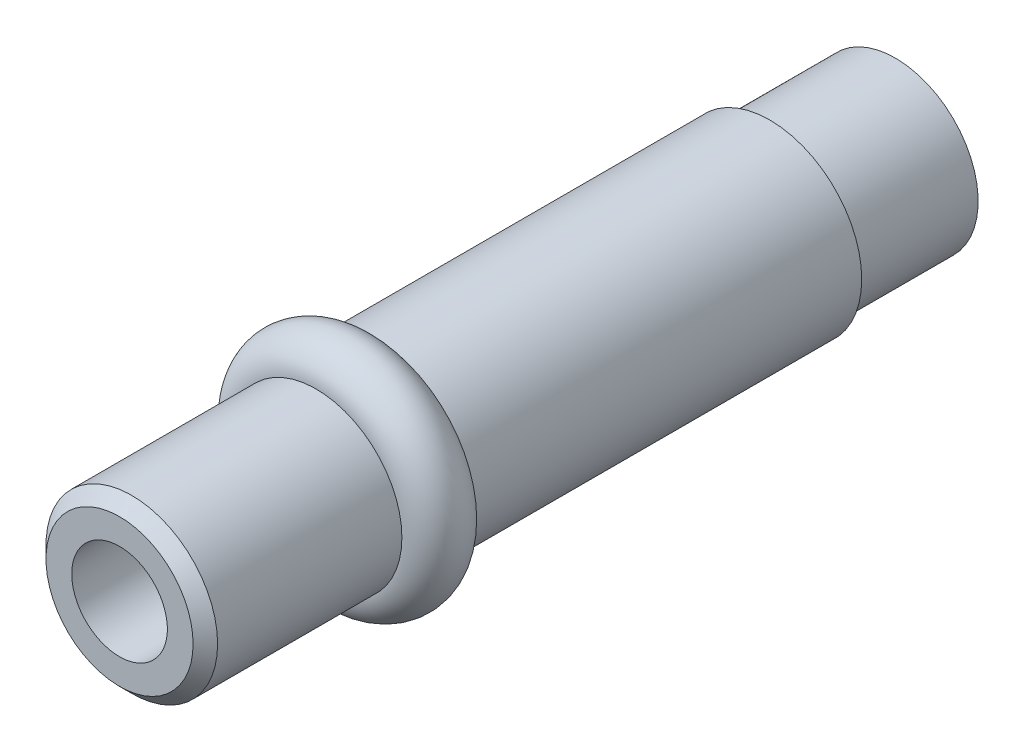
SolidWorks part; units mm, degrees
material "Plain Carbon Steel"
ref_plane "Front Plane" through (0, 0, 0) normal (0, 0, 1) x (1, 0, 0)
ref_plane "Top Plane" through (0, 0, 0) normal (0, 1, 0) x (1, 0, 0)
ref_plane "Right Plane" through (0, 0, 0) normal (1, 0, 0) x (0, 0, -1)
sketch "Sketch1" plane through (0, 0, 0) normal (0, 0, 1) x (1, 0, 0)
  circle A0 centre (0, 0) radius 3.81
  dimension "D1" = 7.62
extrude "Boss-Extrude1" add sketch "Sketch1" along normal blind 32.1564
sketch "Sketch2" plane through (0, 0, 0) normal (0, 0, -1) x (-1, 0, 0)
  circle A0 centre (0, 0) radius 1.9812
  dimension "D1" = 3.9624
extrude "Cut-Extrude1" cut sketch "Sketch2" against normal through all
sketch "Sketch3" plane through (0, 0, 0) normal (0, 0, -1) x (-1, 0, 0)
  circle A0 centre (0, 0) radius 3.429
  circle A1 centre (0, 0) radius 3.81 construction
  circle A2 centre (0, 0) radius 3.81
  dimension "D1" = 6.858
extrude "Cut-Extrude2" cut sketch "Sketch3" against normal blind 5.207
sketch "Sketch4" plane through (0, 0, 32.1564) normal (0, 0, 1) x (1, 0, 0)
  circle A0 centre (0, 0) radius 3.81 construction
  circle A1 centre (0, 0) radius 3.81
  circle A2 centre (0, 0) radius 3.556
  dimension "D1" = 7.112
extrude "Cut-Extrude3" cut sketch "Sketch4" against normal blind 9.652
sketch "Sketch5" plane through (0, 0, 0) normal (0, 1, 0) x (1, 0, 0)
  line L0 (3.81, -22.5044) -> (3.81, -5.207) construction
  line L1 (3.556, -32.1564) -> (3.556, -22.5044) construction
  line L2 (-3.81, -22.5044) -> (3.81, -22.5044) construction
  line L3 (3.556, -24.0097) -> (3.2696, -21.4528)
  line L4 (3.2696, -21.4528) -> (3.81, -21.4528)
  arc A0 (3.81, -21.4528) -> (3.556, -24.0097) centre (3.5324, -22.7163) cw
  point P3 (4.826, -22.7163)
  point P8 (0, -22.5044)
  dimension "D1" = 4.826
revolve "Revolve1" add sketch "Sketch5" angle 360 about axis through (0, 0, 32.1564) along (0, 0, -1)
chamfer "Chamfer1" distance 0.508 angle 45 1 edges at (3.556, 0, 32.1564)
